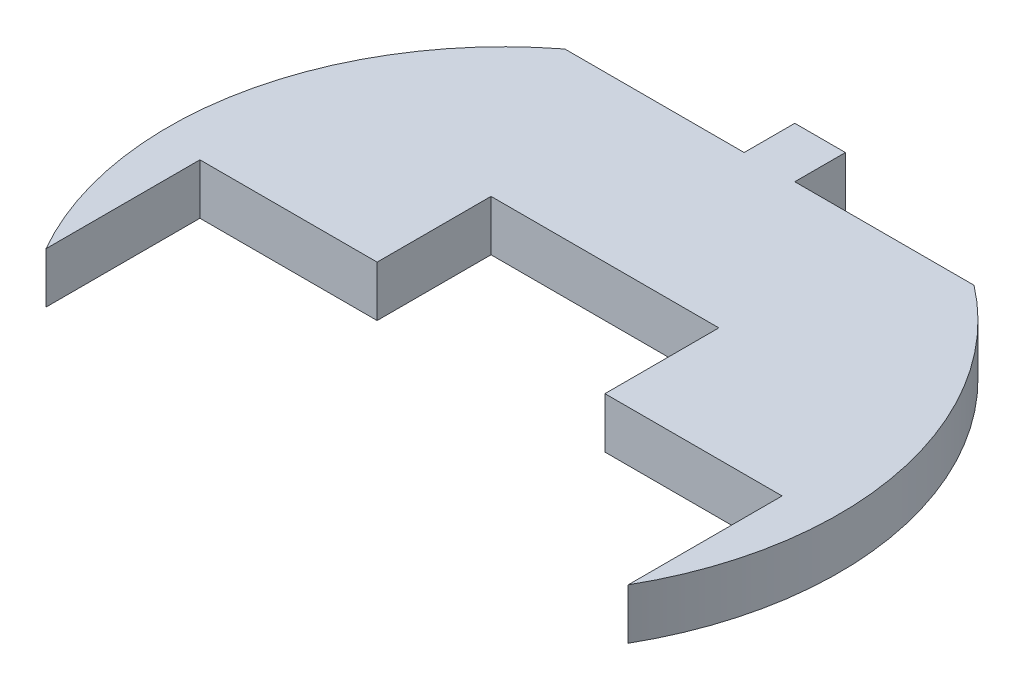
SolidWorks part; units mm, degrees
ref_plane "Piano frontale" through (0, 0, 0) normal (0, 0, 1) x (1, 0, 0)
ref_plane "Piano superiore" through (0, 0, 0) normal (0, 1, 0) x (1, 0, 0)
ref_plane "Piano destro" through (0, 0, 0) normal (1, 0, 0) x (0, 0, -1)
sketch "Schizzo1" plane through (0, 0, 0) normal (0, 1, 0) x (1, 0, 0)
  line L0 (-16.1632, 16) -> (16.1632, 16)
  line L1 (-2, 16) -> (-2, 20)
  line L2 (-2, 20) -> (2, 20)
  line L3 (2, 20) -> (2, 16)
  line L4 (-23, -18.1624) -> (-23, -6)
  line L5 (-23, -6) -> (-9, -6)
  line L6 (-9, -6) -> (-9, 3)
  line L7 (-9, 3) -> (9, 3)
  line L8 (9, 3) -> (9, -6)
  line L9 (9, -6) -> (23, -6)
  line L10 (23, -6) -> (23, -18.1624)
  arc A0 (-23, -18.1624) -> (23, -18.1624) centre (0, -5) cw
  point P17 (0, 20)
  point P19 (0, 3)
  dimension "D1" = 26.5
  dimension "D9" = 23
  dimension "D2" = 4
  dimension "D3" = 4
  dimension "D4" = 9
  dimension "D5" = 9
  dimension "D6" = 23
  dimension "D7" = 5
  dimension "D8" = 3
  dimension "D10" = 21
  dimension "D11" = 18
extrude "Estrusione-Estrusione1" add sketch "Schizzo1" along normal blind 4 contours A0 L4 L5 L6 L7 L8 L9 L10 L0 | L3 L2 L1 L0
